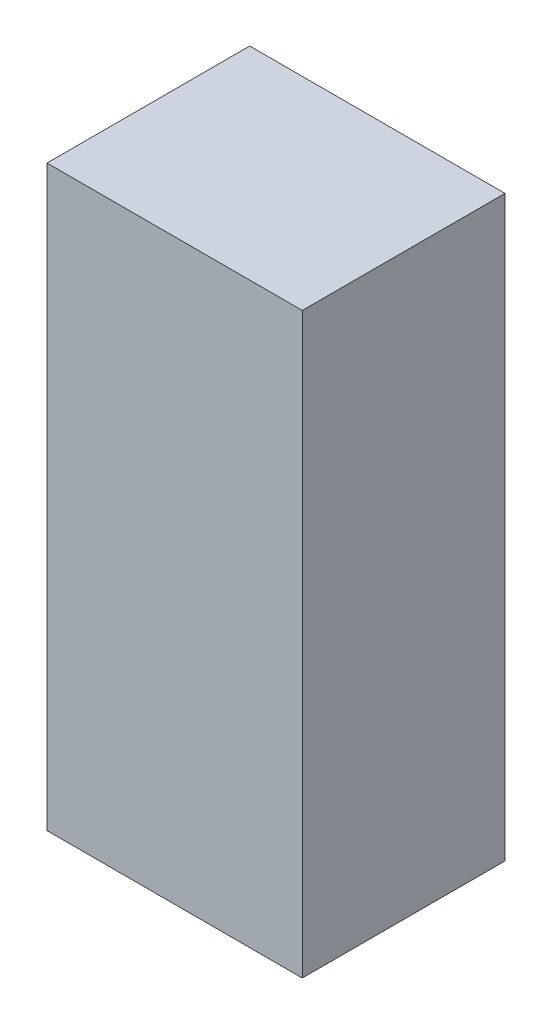
SolidWorks part; units mm, degrees
ref_plane "Plano frontal" through (0, 0, 0) normal (1, 0, 0) x (0, 1, 0)
ref_plane "Plano superior" through (0, 0, 0) normal (0, 0, 1) x (0, 1, 0)
ref_plane "Plano direito" through (0, 0, 0) normal (0, 1, 0) x (-1, 0, 0)
sketch "Esboço1" plane through (0, 0, 0) normal (0, 0, 1) x (0, 1, 0)
  line L1 (-38.5, -17) -> (38.5, -17)
  line L2 (-38.5, -17) -> (-38.5, 17)
  line L3 (-38.5, 17) -> (38.5, 17)
  line L4 (38.5, -17) -> (38.5, 17)
  line L5 (-38.5, -17) -> (38.5, 17) construction
  line L6 (-38.5, 17) -> (38.5, -17) construction
  point P0 (0, 0)
  dimension "D1" = 34
  dimension "D2" = 77
extrude "Ressalto-extrusão1" add sketch "Esboço1" along normal blind 27
